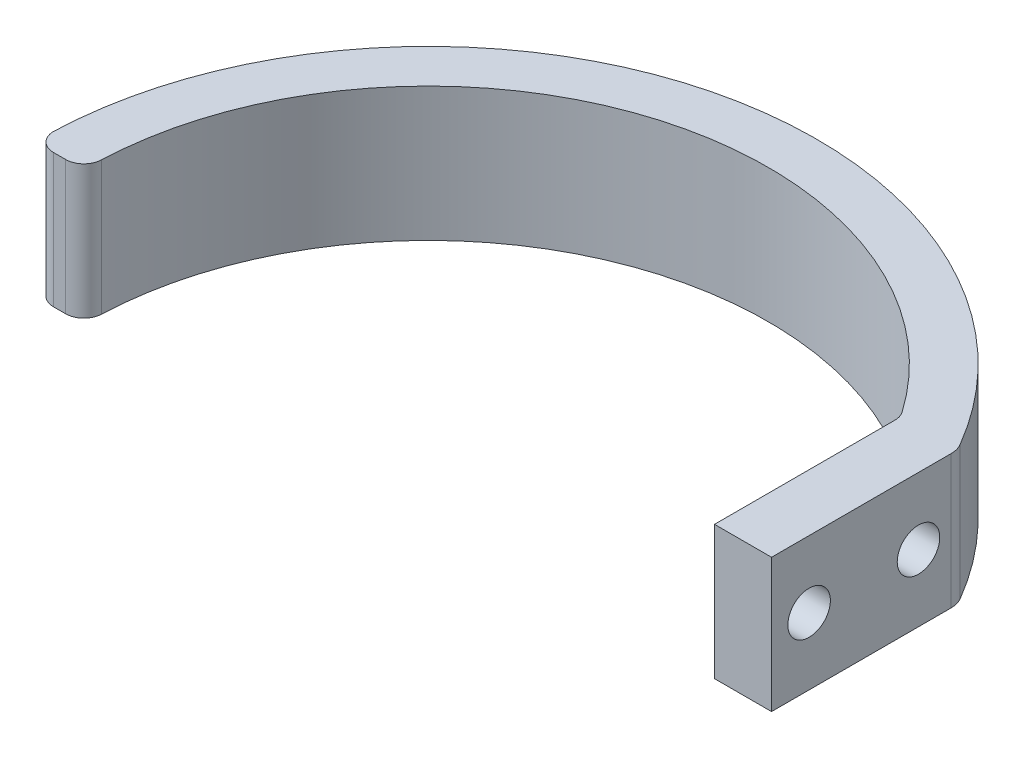
SolidWorks part; units mm, degrees
ref_plane "Front Plane" through (0, 0, 0) normal (0, 0, 1) x (1, 0, 0)
ref_plane "Top Plane" through (0, 0, 0) normal (0, 1, 0) x (1, 0, 0)
ref_plane "Right Plane" through (0, 0, 0) normal (1, 0, 0) x (0, 0, -1)
sketch "Sketch1" plane through (0, 0, 0) normal (0, 1, 0) x (1, 0, 0)
  line L0 (-31.9981, -0.3484) -> (-27.9981, -0.3484)
  line L1 (31.9981, 0.3484) -> (27.9981, 0.3484)
  arc A0 (31.9981, 0.3484) -> (-31.9981, -0.3484) centre (0, 0) ccw
  arc A1 (-27.9981, -0.3484) -> (27.9981, 0.3484) centre (0, 0) cw
  dimension "D1" = 32
  dimension "D2" = 4
extrude "Boss-Extrude1" add sketch "Sketch1" along normal blind 11 contours A1 L1 A0 L0
sketch "Sketch2" plane through (0, 11, 0) normal (0, 1, 0) x (1, 0, 0)
  line L1 (31.9981, 0.3484) -> (23.2127, 0.3484)
  line L2 (31.9981, 0.3484) -> (31.9981, 15.6584)
  line L3 (31.9981, 15.6584) -> (23.2127, 15.6584)
  line L4 (23.2127, 0.3484) -> (23.2127, 15.6584)
  arc A0 (27.9981, 0.3484) -> (-27.9981, -0.3484) centre (0, 0) ccw construction
  dimension "D1" = 15.31
  dimension "D2" = 8.7854
extrude "Boss-Extrude2" add sketch "Sketch2" against normal through all
sketch "Sketch3" plane through (31.9981, 0, 0) normal (1, 0, 0) x (0, 0, -1)
  line L1 (0.3484, 11) -> (15.6584, 11) construction
  circle A0 centre (3.4394, 5.5) radius 1.75
  circle A1 centre (12.4394, 5.5) radius 1.75
  dimension "D1" = 3.5
  dimension "D3" = 5.5
  dimension "D2" = 3.5
  dimension "D4" = 9
extrude "Cut-Extrude3" cut sketch "Sketch3" against normal up to next
fillet "Fillet2" radius 1.5 1 edges at (23.2127, 5.5, -15.6584)
fillet "Fillet4" radius 1.5 2 edges at (-31.9981, 5.5, 0.3484) (-27.9981, 5.5, 0.3484)
sketch "Sketch5" plane through (0, 11, 0) normal (0, 1, 0) x (1, 0, 0)
  line L0 (31.9981, 0.3484) -> (23.2127, 0.3484) construction
  line L1 (31.9981, 15.6584) -> (27.9072, 15.6584)
  line L2 (31.9981, 15.6584) -> (31.9981, 0.3484)
  line L3 (31.9981, 0.3484) -> (27.9072, 0.3484)
  line L4 (27.9072, 15.6584) -> (27.9072, 0.3484)
extrude "Cut-Extrude4" cut sketch "Sketch5" against normal up to next
fillet "Fillet6" radius 2 1 edges at (27.9072, 5.5, -15.6584)
